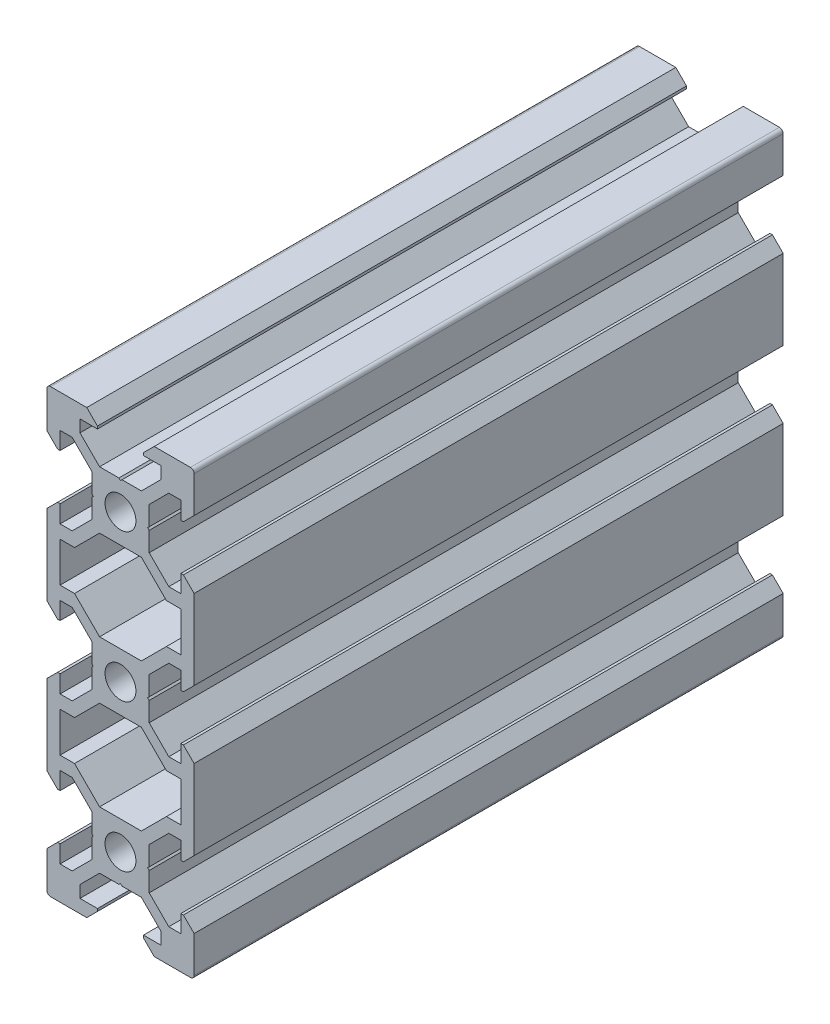
SolidWorks part; units mm, degrees
material "6061-T6 (SS)"
ref_plane "Front Plane" through (0, 0, 0) normal (0, 0, 1) x (1, 0, 0)
ref_plane "Top Plane" through (0, 0, 0) normal (0, 1, 0) x (1, 0, 0)
ref_plane "Right Plane" through (0, 0, 0) normal (1, 0, 0) x (0, 0, -1)
ref_plane "Plane1" through (0, 0, 500) normal (0, 0, 1) x (1, 0, 0)
sketch "Sketch1" plane through (0, 0, 500) normal (0, 0, 1) x (1, 0, 0)
  line L0 (6.5607, 14.5) -> (3.9, 17.1607)
  line L1 (3.9, 17.1607) -> (3.9, 19.79)
  line L2 (3.9, 19.79) -> (3.69, 20)
  line L3 (3.69, 20) -> (3.9, 20.21)
  line L4 (3.9, 20.21) -> (3.9, 22.8393)
  line L5 (3.9, 22.8393) -> (6.5607, 25.5)
  line L6 (6.5607, 25.5) -> (8.2, 25.5)
  line L7 (8.2, 25.5) -> (8.2, 23.125)
  line L8 (8.2, 23.125) -> (8.545, 23.125)
  line L9 (8.545, 23.125) -> (10, 24.58)
  line L10 (10, 24.58) -> (10, 29.5)
  line L11 (9.5, 30) -> (4.58, 30)
  line L12 (4.58, 30) -> (3.125, 28.545)
  line L13 (3.125, 28.545) -> (3.125, 28.2)
  line L14 (3.125, 28.2) -> (5.5, 28.2)
  line L15 (5.5, 28.2) -> (5.5, 26.5607)
  line L16 (5.5, 26.5607) -> (2.8393, 23.9)
  line L17 (2.8393, 23.9) -> (0.21, 23.9)
  line L18 (0.21, 23.9) -> (0, 23.69)
  line L19 (0, 23.69) -> (-0.21, 23.9)
  line L20 (-0.21, 23.9) -> (-2.8393, 23.9)
  line L21 (-2.8393, 23.9) -> (-5.5, 26.5607)
  line L22 (-5.5, 26.5607) -> (-5.5, 28.2)
  line L23 (-5.5, 28.2) -> (-3.125, 28.2)
  line L24 (-3.125, 28.2) -> (-3.125, 28.545)
  line L25 (-3.125, 28.545) -> (-4.58, 30)
  line L26 (-4.58, 30) -> (-9.5, 30)
  line L27 (-10, 29.5) -> (-10, 24.58)
  line L28 (-10, 24.58) -> (-8.545, 23.125)
  line L29 (-8.545, 23.125) -> (-8.2, 23.125)
  line L30 (-8.2, 23.125) -> (-8.2, 25.5)
  line L31 (-8.2, 25.5) -> (-6.5607, 25.5)
  line L32 (-6.5607, 25.5) -> (-3.9, 22.8393)
  line L33 (-3.9, 22.8393) -> (-3.9, 20.21)
  line L34 (-3.9, 20.21) -> (-3.69, 20)
  line L35 (-3.69, 20) -> (-3.9, 19.79)
  line L36 (-3.9, 19.79) -> (-3.9, 17.1607)
  line L37 (-3.9, 17.1607) -> (-6.5607, 14.5)
  line L38 (-6.5607, 14.5) -> (-8.2, 14.5)
  line L39 (-8.2, 14.5) -> (-8.2, 16.875)
  line L40 (-8.2, 16.875) -> (-8.545, 16.875)
  line L41 (-8.545, 16.875) -> (-10, 15.42)
  line L42 (-10, 15.42) -> (-10, 4.58)
  line L43 (-10, 4.58) -> (-8.545, 3.125)
  line L44 (-8.545, 3.125) -> (-8.2, 3.125)
  line L45 (-8.2, 3.125) -> (-8.2, 5.5)
  line L46 (-8.2, 5.5) -> (-6.5607, 5.5)
  line L47 (-6.5607, 5.5) -> (-3.9, 2.8393)
  line L48 (-3.9, 2.8393) -> (-3.9, 0.21)
  line L49 (-3.9, 0.21) -> (-3.69, 0)
  line L50 (-3.69, 0) -> (-3.9, -0.21)
  line L51 (-3.9, -0.21) -> (-3.9, -2.8393)
  line L52 (-3.9, -2.8393) -> (-6.5607, -5.5)
  line L53 (-6.5607, -5.5) -> (-8.2, -5.5)
  line L54 (-8.2, -5.5) -> (-8.2, -3.125)
  line L55 (-8.2, -3.125) -> (-8.545, -3.125)
  line L56 (-8.545, -3.125) -> (-10, -4.58)
  line L57 (-10, -4.58) -> (-10, -15.42)
  line L58 (-10, -15.42) -> (-8.545, -16.875)
  line L59 (-8.545, -16.875) -> (-8.2, -16.875)
  line L60 (-8.2, -16.875) -> (-8.2, -14.5)
  line L61 (-8.2, -14.5) -> (-6.5607, -14.5)
  line L62 (-6.5607, -14.5) -> (-3.9, -17.1607)
  line L63 (-3.9, -17.1607) -> (-3.9, -19.79)
  line L64 (-3.9, -19.79) -> (-3.69, -20)
  line L65 (-3.69, -20) -> (-3.9, -20.21)
  line L66 (-3.9, -20.21) -> (-3.9, -22.8393)
  line L67 (-3.9, -22.8393) -> (-6.5607, -25.5)
  line L68 (-6.5607, -25.5) -> (-8.2, -25.5)
  line L69 (-8.2, -25.5) -> (-8.2, -23.125)
  line L70 (-8.2, -23.125) -> (-8.545, -23.125)
  line L71 (-8.545, -23.125) -> (-10, -24.58)
  line L72 (-10, -24.58) -> (-10, -29.5)
  line L73 (-9.5, -30) -> (-4.58, -30)
  line L74 (-4.58, -30) -> (-3.125, -28.545)
  line L75 (-3.125, -28.545) -> (-3.125, -28.2)
  line L76 (-3.125, -28.2) -> (-5.5, -28.2)
  line L77 (-5.5, -28.2) -> (-5.5, -26.5607)
  line L78 (-5.5, -26.5607) -> (-2.8393, -23.9)
  line L79 (-2.8393, -23.9) -> (-0.21, -23.9)
  line L80 (-0.21, -23.9) -> (0, -23.69)
  line L81 (0, -23.69) -> (0.21, -23.9)
  line L82 (0.21, -23.9) -> (2.8393, -23.9)
  line L83 (2.8393, -23.9) -> (5.5, -26.5607)
  line L84 (5.5, -26.5607) -> (5.5, -28.2)
  line L85 (5.5, -28.2) -> (3.125, -28.2)
  line L86 (3.125, -28.2) -> (3.125, -28.545)
  line L87 (3.125, -28.545) -> (4.58, -30)
  line L88 (4.58, -30) -> (9.5, -30)
  line L89 (10, -29.5) -> (10, -24.58)
  line L90 (10, -24.58) -> (8.545, -23.125)
  line L91 (8.545, -23.125) -> (8.2, -23.125)
  line L92 (8.2, -23.125) -> (8.2, -25.5)
  line L93 (8.2, -25.5) -> (6.5607, -25.5)
  line L94 (6.5607, -25.5) -> (3.9, -22.8393)
  line L95 (3.9, -22.8393) -> (3.9, -20.21)
  line L96 (3.9, -20.21) -> (3.69, -20)
  line L97 (3.69, -20) -> (3.9, -19.79)
  line L98 (3.9, -19.79) -> (3.9, -17.1607)
  line L99 (3.9, -17.1607) -> (6.5607, -14.5)
  line L100 (6.5607, -14.5) -> (8.2, -14.5)
  line L101 (8.2, -14.5) -> (8.2, -16.875)
  line L102 (8.2, -16.875) -> (8.545, -16.875)
  line L103 (8.545, -16.875) -> (10, -15.42)
  line L104 (10, -15.42) -> (10, -4.58)
  line L105 (10, -4.58) -> (8.545, -3.125)
  line L106 (8.545, -3.125) -> (8.2, -3.125)
  line L107 (8.2, -3.125) -> (8.2, -5.5)
  line L108 (8.2, -5.5) -> (6.5607, -5.5)
  line L109 (6.5607, -5.5) -> (3.9, -2.8393)
  line L110 (3.9, -2.8393) -> (3.9, -0.21)
  line L111 (3.9, -0.21) -> (3.69, 0)
  line L112 (3.69, 0) -> (3.9, 0.21)
  line L113 (3.9, 0.21) -> (3.9, 2.8393)
  line L114 (3.9, 2.8393) -> (6.5607, 5.5)
  line L115 (6.5607, 5.5) -> (8.2, 5.5)
  line L116 (8.2, 5.5) -> (8.2, 3.125)
  line L117 (8.2, 3.125) -> (8.545, 3.125)
  line L118 (8.545, 3.125) -> (10, 4.58)
  line L119 (10, 4.58) -> (10, 15.42)
  line L120 (10, 15.42) -> (8.545, 16.875)
  line L121 (8.545, 16.875) -> (8.2, 16.875)
  line L122 (8.2, 16.875) -> (8.2, 14.5)
  line L123 (8.2, 14.5) -> (6.5607, 14.5)
  line L124 (2.8393, 3.9) -> (-2.8393, 3.9)
  line L125 (-2.8393, 3.9) -> (-6.2393, 7.3)
  line L126 (-6.2393, 7.3) -> (-8.2, 7.3)
  line L127 (-8.2, 7.3) -> (-8.2, 12.7)
  line L128 (-8.2, 12.7) -> (-6.2393, 12.7)
  line L129 (-6.2393, 12.7) -> (-2.8393, 16.1)
  line L130 (-2.8393, 16.1) -> (2.8393, 16.1)
  line L131 (2.8393, 16.1) -> (6.2393, 12.7)
  line L132 (6.2393, 12.7) -> (8.2, 12.7)
  line L133 (8.2, 12.7) -> (8.2, 7.3)
  line L134 (8.2, 7.3) -> (6.2393, 7.3)
  line L135 (6.2393, 7.3) -> (2.8393, 3.9)
  line L136 (2.8393, -16.1) -> (-2.8393, -16.1)
  line L137 (-2.8393, -16.1) -> (-6.2393, -12.7)
  line L138 (-6.2393, -12.7) -> (-8.2, -12.7)
  line L139 (-8.2, -12.7) -> (-8.2, -7.3)
  line L140 (-8.2, -7.3) -> (-6.2393, -7.3)
  line L141 (-6.2393, -7.3) -> (-2.8393, -3.9)
  line L142 (-2.8393, -3.9) -> (2.8393, -3.9)
  line L143 (2.8393, -3.9) -> (6.2393, -7.3)
  line L144 (6.2393, -7.3) -> (8.2, -7.3)
  line L145 (8.2, -7.3) -> (8.2, -12.7)
  line L146 (8.2, -12.7) -> (6.2393, -12.7)
  line L147 (6.2393, -12.7) -> (2.8393, -16.1)
  circle A0 centre (0, 20) radius 2.1
  circle A1 centre (0, 0) radius 2.1
  circle A2 centre (0, -20) radius 2.1
  arc A3 (10, 29.5) -> (9.5, 30) centre (9.5, 29.5) ccw
  arc A4 (-9.5, 30) -> (-10, 29.5) centre (-9.5, 29.5) ccw
  arc A5 (-10, -29.5) -> (-9.5, -30) centre (-9.5, -29.5) ccw
  arc A6 (9.5, -30) -> (10, -29.5) centre (9.5, -29.5) ccw
extrude "Boss-Extrude1" add sketch "Sketch1" against normal blind 80
